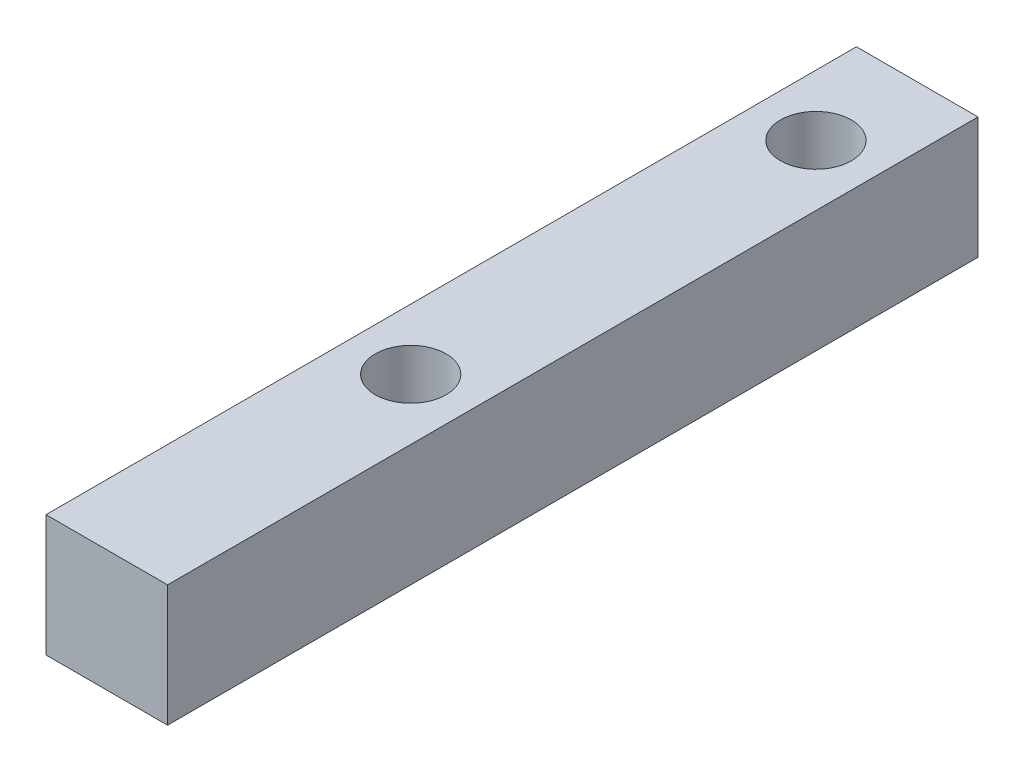
SolidWorks part; units mm, degrees
material "ABS"
ref_plane "前视基准面" through (0, 0, 0) normal (0, 0, 1) x (1, 0, 0)
ref_plane "上视基准面" through (0, 0, 0) normal (0, 1, 0) x (1, 0, 0)
ref_plane "右视基准面" through (0, 0, 0) normal (1, 0, 0) x (0, 0, -1)
other "Configuration Table"
sketch "草图1" plane through (0, 0, 0) normal (0, 1, 0) x (1, 0, 0)
  line L1 (-3, 20) -> (3, 20)
  line L2 (-3, 20) -> (-3, -20)
  line L3 (-3, -20) -> (3, -20)
  line L4 (3, 20) -> (3, -20)
  line L5 (-3, 20) -> (3, -20) construction
  line L6 (-3, -20) -> (3, 20) construction
  circle A0 centre (0, 15) radius 1.75
  circle A1 centre (0, -5) radius 1.75
  point P0 (0, 0)
  dimension "D3" = 3.5
  dimension "D1" = 6
  dimension "D2" = 40
  dimension "D4" = 20
  dimension "D5" = 5
extrude "凸台-拉伸1" add sketch "草图1" along normal blind 6
